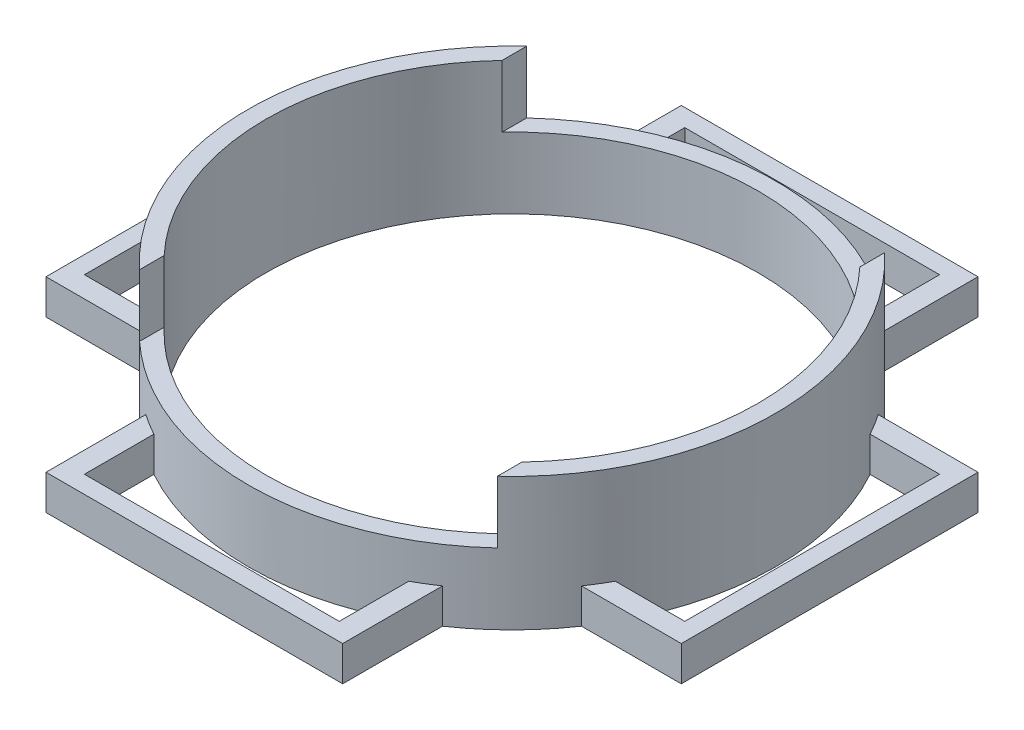
SolidWorks part; units mm, degrees
ref_plane "Alzado" through (0, 0, 0) normal (0, 0, 1) x (1, 0, 0)
ref_plane "Planta" through (0, 0, 0) normal (0, 1, 0) x (1, 0, 0)
ref_plane "Vista lateral" through (0, 0, 0) normal (1, 0, 0) x (0, 0, -1)
sketch "Croquis1" plane through (0, 0, 0) normal (0, 0, 1) x (1, 0, 0)
  line L0 (0, 5.9417) -> (0, -6.3917) construction
  line L2 (14.1, 3.81) -> (15.1, 3.81)
  line L3 (14.1, 3.81) -> (14.1, -3.81)
  line L4 (14.1, -3.81) -> (15.1, -3.81)
  line L5 (15.1, 3.81) -> (15.1, -3.81)
  line L6 (14.1, 3.81) -> (15.1, -3.81) construction
  line L7 (14.1, -3.81) -> (15.1, 3.81) construction
  point P3 (14.6, 0)
  dimension "D1" = 1
  dimension "D2" = 7.62
  dimension "D3" = 14.6
revolve "Revolución1" add sketch "Croquis1" angle 360 about L0
sketch "Croquis2" plane through (0, 0, 0) normal (0, 1, 0) x (1, 0, 0)
  line L0 (8.5, -18.2) -> (-8.5, -18.2)
  line L1 (8.5, -18.2) -> (8.5, -12.4804)
  line L2 (-8.5, -18.2) -> (-8.5, -12.4804)
  line L3 (-7.3, -17.2) -> (-7.3, -12.4804)
  line L4 (7.3, -17.2) -> (-7.3, -17.2)
  line L5 (7.3, -17.2) -> (7.3, -12.4804)
  line L6 (8.5, -12.4804) -> (7.3, -12.4804)
  line L7 (-7.3, -12.4804) -> (-8.5, -12.4804)
  circle A0 centre (0, 0) radius 15.1 construction
  point P2 (0, -18.2)
  dimension "D1" = 17
  dimension "D2" = 1
  dimension "D3" = 17.2
  dimension "D4" = 1.2
  dimension "D5" = 1.2
extrude "Saliente-Extruir1" add sketch "Croquis2" along normal blind 2 from surface at -3.81 starting at face at (0, -3.81, 15.1)
sketch "Croquis3" plane through (0, 0, 0) normal (0, 0, 1) x (1, 0, 0)
  line L0 (0, 11.4718) -> (0, -13.5546) construction
pattern_circular "MatrizC1" count 4 every 90 about axis through (0, 0, 0) along (0, 1, 0) of "Saliente-Extruir1"
sketch "Croquis4" plane through (0, 0, 0) normal (0, 0, 1) x (1, 0, 0)
  line L1 (-10.25, 3.81) -> (10.25, 3.81)
  line L2 (-10.25, 3.81) -> (-10.25, 0.25)
  line L3 (-10.25, 0.25) -> (10.25, 0.25)
  line L4 (10.25, 3.81) -> (10.25, 0.25)
  line L6 (15.1, 3.81) -> (-15.1, 3.81) construction
  point P4 (0, 0.25)
  point P6 (0, 0)
  dimension "D1" = 3.56
  dimension "D2" = 20.5
extrude "Cortar-Extruir1" cut sketch "Croquis4" against normal through all both and the other way through all
